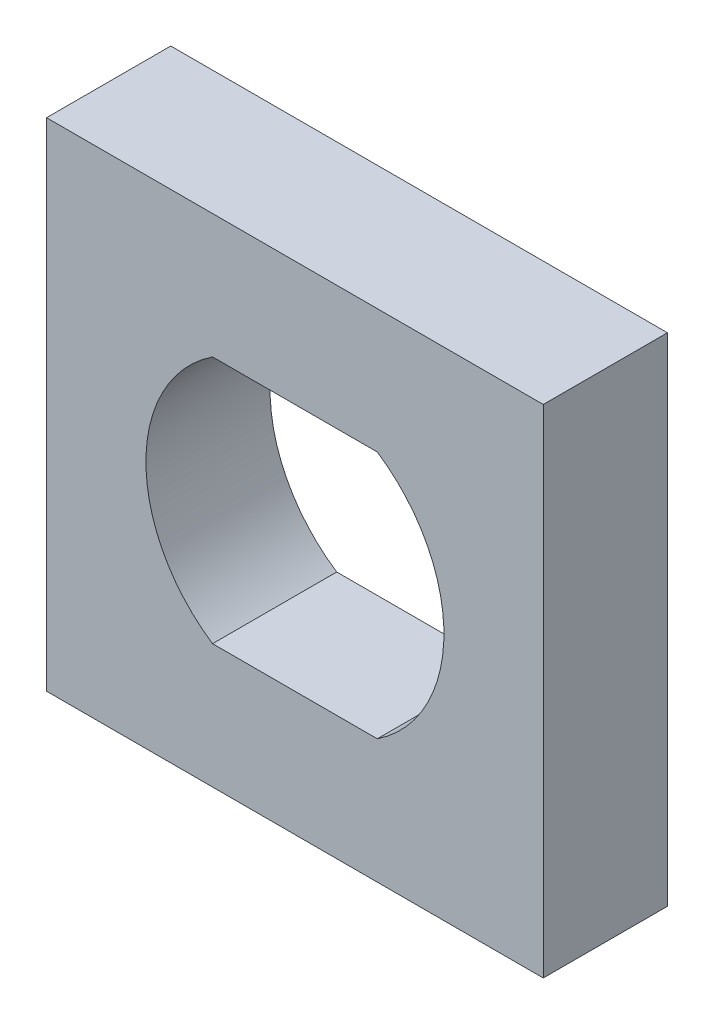
SolidWorks part; units mm, degrees
ref_plane "Front Plane" through (0, 0, 0) normal (0, 0, 1) x (1, 0, 0)
ref_plane "Top Plane" through (0, 0, 0) normal (0, 1, 0) x (1, 0, 0)
ref_plane "Right Plane" through (0, 0, 0) normal (1, 0, 0) x (0, 0, -1)
sketch "Sketch1" plane through (0, 0, 0) normal (0, 0, 1) x (1, 0, 0)
  line L0 (-3.3166, 5) -> (3.3166, 5)
  line L1 (-10, 10) -> (10, 10)
  line L2 (-10, 10) -> (-10, -10)
  line L3 (-10, -10) -> (10, -10)
  line L4 (10, 10) -> (10, -10)
  line L5 (-3.3166, -5) -> (3.3166, -5)
  line L6 (0, 5) -> (0, -5) construction
  line L7 (-10, -10) -> (10, 10) construction
  circle A0 centre (0, 0) radius 6
  point P13 (0, 0)
  dimension "D2" = 12
  dimension "D1" = 10
  dimension "D3" = 20
  dimension "D4" = 20
extrude "Boss-Extrude1" add sketch "Sketch1" along normal blind 5 contours L4 L1 L2 L3 A0 | L0 A0 | L5 A0
